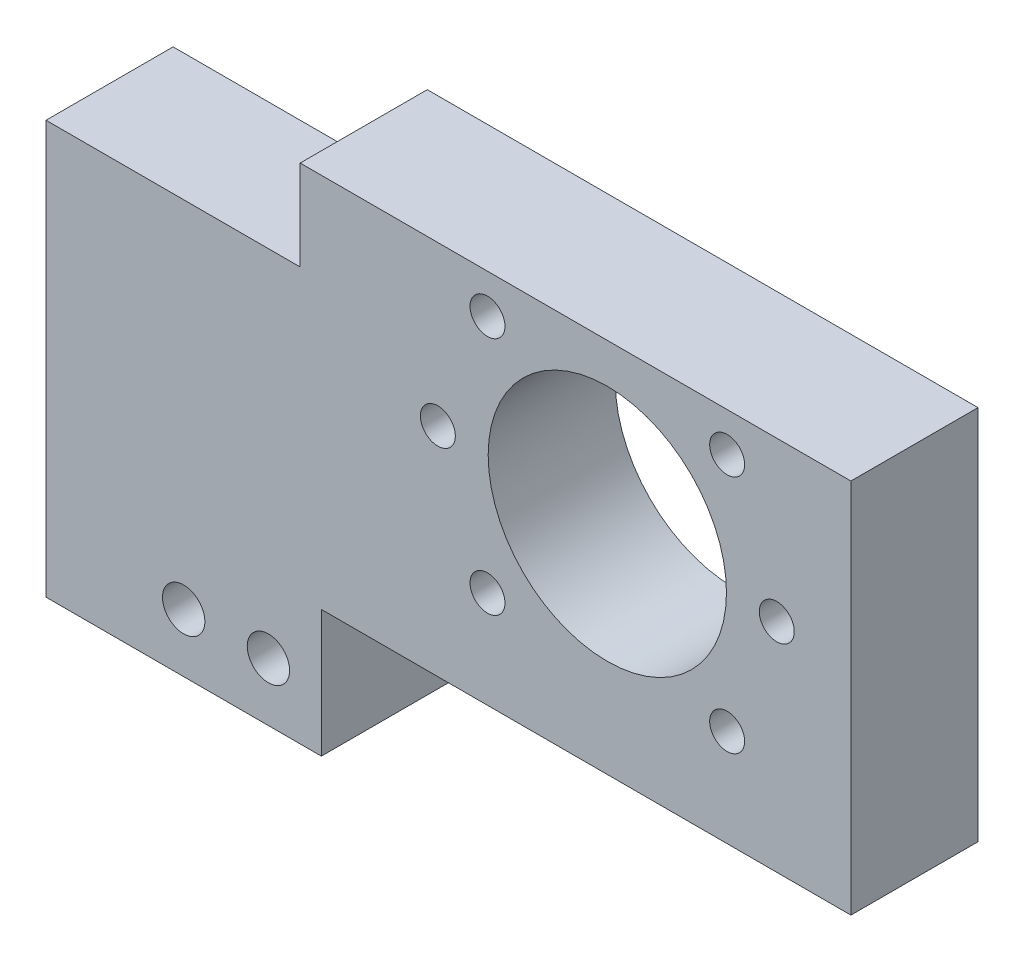
SolidWorks part; units mm, degrees
ref_plane "前视基准面" through (0, 0, 0) normal (0, 0, 1) x (1, 0, 0)
ref_plane "上视基准面" through (0, 0, 0) normal (0, 1, 0) x (1, 0, 0)
ref_plane "右视基准面" through (0, 0, 0) normal (1, 0, 0) x (0, 0, -1)
other "Configuration Table"
sketch "草图1" plane through (0, 0, 0) normal (0, 0, 1) x (1, 0, 0)
  line L1 (-35, -15) -> (35, -15)
  line L2 (-35, -15) -> (-35, 15)
  line L3 (-35, 15) -> (35, 15)
  line L4 (35, -15) -> (35, 15)
  line L5 (0, 15) -> (0, -15) construction
  line L6 (-35, 0) -> (35, 0) construction
  point P0 (0, 0)
  dimension "D1" = 70
  dimension "D2" = 30
extrude "凸台-拉伸1" add sketch "草图1" along normal blind 27
sketch "草图2" plane through (0, 0, 27) normal (0, 0, 1) x (1, 0, 0)
  line L0 (35, -15) -> (35, 15) construction
  line L1 (-35, 15) -> (-35, -15) construction
  line L2 (35, -15) -> (35, 15)
  line L3 (35, 15) -> (28.2288, 15)
  line L6 (-35, -15) -> (35, -15) construction
  line L7 (28.2288, -15) -> (35, -15)
  arc A0 (28.2288, -15) -> (28.2288, 15) centre (15, 0) ccw
  point P8 (-35, 0)
  line M6 (35, -15) -> (35, 15)
  line M7 (35, 15) -> (-35, 15)
  line M9 (-35, -15) -> (35, -15)
  dimension "D1" = 40
extrude "切除-拉伸1" cut sketch "草图2" against normal through all contours A0 M9 M6 | A0 L2 M7
sketch "草图3" plane through (0, 0, 27) normal (0, 0, 1) x (1, 0, 0)
  line L0 (15, 0) -> (31, 0) construction
  line L1 (15, 0) -> (26.3137, 11.3137) construction
  line L2 (15, 0) -> (15, -16) construction
  circle A0 centre (31, 0) radius 1.65
  circle A1 centre (15, 0) radius 16 construction
  circle A2 centre (26.3137, 11.3137) radius 1.65
  circle A3 centre (26.3137, -11.3137) radius 1.65
  circle A4 centre (3.6863, 11.3137) radius 1.65
  circle A5 centre (3.6863, -11.3137) radius 1.65
  circle A6 centre (-1, 0) radius 1.65
  dimension "D1" = 32
  dimension "D3" = 3.3
  dimension "D4" = 3.3
  dimension "D5" = 3.3
  dimension "D2" = 45
extrude "切除-拉伸2" cut sketch "草图3" against normal through all
sketch "草图4" plane through (0, 0, 27) normal (0, 0, 1) x (1, 0, 0)
  line L1 (-35, 15) -> (-14, 15)
  line L2 (-35, 15) -> (-35, 6.5)
  line L3 (-35, 6.5) -> (-14, 6.5)
  line L4 (-14, 15) -> (-14, 6.5)
  dimension "D1" = 8.5
  dimension "D2" = 21
extrude "切除-拉伸3" cut sketch "草图4" against normal through all
sketch "草图7" plane through (0, 0, 0) normal (0, 0, -1) x (-1, 0, 0)
  circle A0 centre (-15, 0) radius 11.25
  dimension "D1" = 22.5
extrude "切除-拉伸5" cut sketch "草图7" against normal through all
sketch "草图8" plane through (0, 0, 0) normal (0, 0, -1) x (-1, 0, 0)
  line L0 (35, -15) -> (-28.2288, -15) construction
  line L1 (35, 6.5) -> (13.5, 6.5)
  line L2 (35, 6.5) -> (35, -15)
  line L3 (35, -15) -> (13.5, -15)
  line L4 (13.5, 6.5) -> (13.5, -15)
extrude "凸台-拉伸2" add sketch "草图8" along normal blind 8
sketch "草图10" plane through (0, -15, 0) normal (0, -1, 0) x (1, 0, 0)
  line L0 (-35, 27) -> (-35, -8) construction
  line L1 (-32.5, 3.95) -> (-17.5, 3.95) construction
  line L2 (-32.5, 3.95) -> (-32.5, 19.95) construction
  line L3 (-32.5, 19.95) -> (-17.5, 19.95) construction
  line L4 (-17.5, 3.95) -> (-17.5, 19.95) construction
  line L5 (-13.5, -8) -> (-35, -8) construction
  circle A0 centre (-32.5, 3.95) radius 1.5 construction
  circle A1 centre (-17.5, 3.95) radius 1.5 construction
  circle A2 centre (-17.5, 19.95) radius 1.5
  circle A3 centre (-32.5, 19.95) radius 1.5
  dimension "D5" = 3
  dimension "D1" = 2.5
  dimension "D2" = 11.95
  dimension "D3" = 16
  dimension "D4" = 15
extrude "切除-拉伸6" cut sketch "草图10" against normal through all
sketch "草图12" plane through (-35, 0, 0) normal (-1, 0, 0) x (0, 0, 1)
  line L4 (27, -15) -> (27, 6.5)
  line L5 (27, 6.5) -> (-8, 6.5)
  line L6 (-8, 6.5) -> (-8, -15)
  line L7 (-8, -15) -> (27, -15)
  line L8 (27, -15) -> (27, 6.5)
  line L9 (27, 6.5) -> (-8, 6.5)
  line L10 (-8, 6.5) -> (-8, -15)
  line L11 (-8, -15) -> (27, -15)
  dimension "D1" = 0
extrude "凸台-拉伸3" add sketch "草图12" along normal blind 3
sketch "草图13" plane through (0, -15, 0) normal (0, -1, 0) x (1, 0, 0)
  circle A1 centre (-32.5, 19.95) radius 3
  circle A2 centre (-17.5, 19.95) radius 3
  dimension "D1" = 6
extrude "切除-拉伸7" cut sketch "草图13" against normal blind 15
sketch "草图14" plane through (0, 0, 27) normal (0, 0, 1) x (1, 0, 0)
  line L1 (28.2288, -15) -> (35, -15)
  line L2 (28.2288, -15) -> (28.2288, -12.9208)
  line L4 (35, -15) -> (35, 0)
  line L5 (28.2288, -9.7067) -> (28.2288, 0)
  line L6 (28.2288, 9.7067) -> (28.2288, 0)
  line L7 (28.2288, 15) -> (35, 15)
  line L8 (28.2288, 15) -> (28.2288, 12.9208)
  line L10 (35, 15) -> (35, 0)
  line L11 (28.2288, 12.9208) -> (28.2288, 9.7067)
  line L12 (28.2288, -12.9208) -> (28.2288, -9.7067)
  arc A0 (28.2288, -15) -> (28.2288, 15) centre (15, 0) ccw construction
  circle A8 centre (31, 0) radius 1.65 construction
  circle A9 centre (31, 0) radius 1.65
  dimension "D1" = 3.2141
  dimension "D2" = 2.0792
  dimension "D3" = 5.2933
  dimension "D4" = 2.0792
  dimension "D5" = 15
extrude "凸台-拉伸4" add sketch "草图14" against normal blind 27
sketch "草图15" plane through (35, 0, 0) normal (1, 0, 0) x (0, 0, -1)
  line L4 (0, -15) -> (0, 15)
  line L5 (0, 15) -> (-27, 15)
  line L6 (-27, 15) -> (-27, -15)
  line L7 (-27, -15) -> (0, -15)
  line L8 (0, -15) -> (0, 15)
  line L9 (0, 15) -> (-27, 15)
  line L10 (-27, 15) -> (-27, -15)
  line L11 (-27, -15) -> (0, -15)
  dimension "D1" = 0
extrude "凸台-拉伸5" add sketch "草图15" along normal blind 3
sketch "草图16" plane through (0, -15, 0) normal (0, -1, 0) x (1, 0, 0)
  line L6 (-13.5, 0) -> (38, 0)
  line L7 (38, 0) -> (38, 27)
  line L8 (38, 27) -> (-38, 27)
  line L9 (-38, 27) -> (-38, -8)
  line L10 (-38, -8) -> (-13.5, -8)
  line L11 (-13.5, -8) -> (-13.5, 0)
  line L12 (-13.5, 0) -> (38, 0)
  line L13 (38, 0) -> (38, 27)
  line L14 (38, 27) -> (-38, 27)
  line L15 (-38, 27) -> (-38, -8)
  line L16 (-38, -8) -> (-13.5, -8)
  line L17 (-13.5, -8) -> (-13.5, 0)
  circle A1 centre (-32.5, 19.95) radius 3 construction
  circle A2 centre (-17.5, 19.95) radius 3 construction
  circle A5 centre (-32.5, 19.95) radius 3
  circle A6 centre (-17.5, 19.95) radius 3
  dimension "D1" = 0
extrude "凸台-拉伸6" add sketch "草图16" along normal blind 5.5
sketch "草图20" plane through (0, 0, 0) normal (0, 0, -1) x (-1, 0, 0)
  line L5 (14, 15) -> (-38, 15)
  line L6 (-38, 15) -> (-38, -20.5)
  line L7 (-38, -20.5) -> (13.5, -20.5)
  line L9 (14, 6.5) -> (14, 15)
  line L10 (14, 15) -> (-38, 15)
  line L11 (-38, 15) -> (-38, -20.5)
  line L14 (14, 6.5) -> (14, 15)
  line L16 (13.5, 6.5) -> (14, 6.5)
  line L17 (13.5, 6.5) -> (14, 6.5)
  line L18 (-38, -20.5) -> (13.5, -20.5)
  line L20 (13.5, -20.5) -> (13.5, 6.5)
  line L21 (13.5, -20.5) -> (13.5, 6.5)
  circle A0 centre (-15, 0) radius 11.25 construction
  circle A1 centre (-15, 0) radius 11.25
  dimension "D1" = 0
sketch "草图22" plane through (0, -20.5, 0) normal (0, -1, 0) x (1, 0, 0)
  line L1 (-38, 27) -> (-12, 27)
  line L2 (-38, 27) -> (-38, 12)
  line L3 (-38, 12) -> (-12, 12)
  line L4 (-12, 27) -> (-12, 12)
  dimension "D1" = 26
  dimension "D2" = 15
extrude "切除-拉伸9" cut sketch "草图22" against normal blind 8
extrude "凸台-拉伸8" add sketch "草图20" along normal blind 8
sketch "草图21" plane through (0, 0, -8) normal (0, 0, -1) x (-1, 0, 0)
  line L0 (-27.816, -16) -> (-2.184, -16)
  line L5 (14, 15) -> (-38, 15) construction
  arc A0 (-2.184, -16) -> (-27.816, -16) centre (-15, 0) ccw
  dimension "D1" = 41
  dimension "D2" = 31
extrude "切除-拉伸8" cut sketch "草图21" against normal blind 8
sketch "草图23" plane through (0, -20.5, 0) normal (0, -1, 0) x (1, 0, 0)
  line L0 (-38, -8) -> (38, -8) construction
  line L1 (-38, 12) -> (-12, 12)
  line L2 (-38, 12) -> (-38, -8)
  line L3 (-38, -8) -> (-12, -8)
  line L4 (-12, 12) -> (-12, -8)
  dimension "D1" = 26
extrude "凸台-拉伸9" add sketch "草图23" along normal blind 17
sketch "草图24" plane through (0, 0, -8) normal (0, 0, -1) x (-1, 0, 0)
  line L0 (12, -20.5) -> (-38, -20.5) construction
  line L2 (12, -37.5) -> (12, -20.5) construction
  circle A0 centre (17, -27) radius 2
  circle A1 centre (25, -27) radius 2
  dimension "D3" = 4
  dimension "D1" = 6.5
  dimension "D2" = 5
  dimension "D4" = 8
extrude "切除-拉伸10" cut sketch "草图24" against normal through all
sketch "草图25" plane through (0, 0, -8) normal (0, 0, -1) x (-1, 0, 0)
  circle A0 centre (17, -27) radius 3.75
  circle A1 centre (25, -27) radius 3.75
  dimension "D1" = 7.5
extrude "切除-拉伸11" cut sketch "草图25" against normal blind 5
sketch "草图26" plane through (0, -37.5, 0) normal (0, -1, 0) x (1, 0, 0)
  line L0 (-12, 12) -> (-38, 12) construction
  line L1 (-38, 12) -> (-38, -8) construction
  circle A0 centre (-31, 7) radius 3.1
  dimension "D1" = 6.2
  dimension "D2" = 5
  dimension "D3" = 7
extrude "切除-拉伸12" cut sketch "草图26" against normal blind 16
sketch "草图27" plane through (0, -21.5, 0) normal (0, -1, 0) x (1, 0, 0)
  circle A0 centre (-31, 7) radius 1.25
  dimension "D1" = 2.5
extrude "切除-拉伸13" cut sketch "草图27" against normal blind 10
sketch "草图28" plane through (0, -37.5, 0) normal (0, -1, 0) x (1, 0, 0)
  line L0 (-38, -8) -> (-12, -8) construction
  line L1 (-32, 4.0657) -> (-30, 4.0657)
  line L2 (-32, 4.0657) -> (-32, -8)
  line L3 (-32, -8) -> (-30, -8)
  line L4 (-30, 4.0657) -> (-30, -8)
  circle A0 centre (-31, 7) radius 3.1 construction
  dimension "D1" = 2
extrude "切除-拉伸14" cut sketch "草图28" against normal blind 16
fillet "圆角1" radius 2 2 edges at (-30, -29.5, 4.0657) (-32, -29.5, 4.0657)
sketch "草图29" plane through (-38, 0, 0) normal (-1, 0, 0) x (0, 0, 1)
  line L0 (-8, 6.5) -> (-8, -37.5) construction
  line L1 (12, -37.5) -> (-8, -37.5)
  line L2 (12, -37.5) -> (12, -32.5)
  line L3 (12, -32.5) -> (-8, -32.5)
  line L4 (-8, -37.5) -> (-8, -32.5)
  dimension "D1" = 5
extrude "切除-拉伸15" cut sketch "草图29" against normal through all
sketch "草图30" plane through (38, 0, 0) normal (1, 0, 0) x (0, 0, -1)
  line L0 (8, 15) -> (-27, 15) construction
  line L1 (8, -32.5) -> (0, -32.5)
  line L2 (8, -32.5) -> (8, 15)
  line L3 (8, 15) -> (0, 15)
  line L4 (0, -32.5) -> (0, 15)
  dimension "D1" = 8
extrude "切除-拉伸16" cut sketch "草图30" against normal through all
sketch "草图31" plane through (-38, 0, 0) normal (-1, 0, 0) x (0, 0, 1)
  line L1 (12, -20.5) -> (27, -20.5)
  line L2 (12, -20.5) -> (12, 15)
  line L3 (12, 15) -> (27, 15)
  line L4 (27, -20.5) -> (27, 15)
extrude "切除-拉伸17" cut sketch "草图31" against normal through all
ref_plane "基准面1" through (38, -20.5, 12) normal (-1, 0, 0) x (0, 0, 1)
